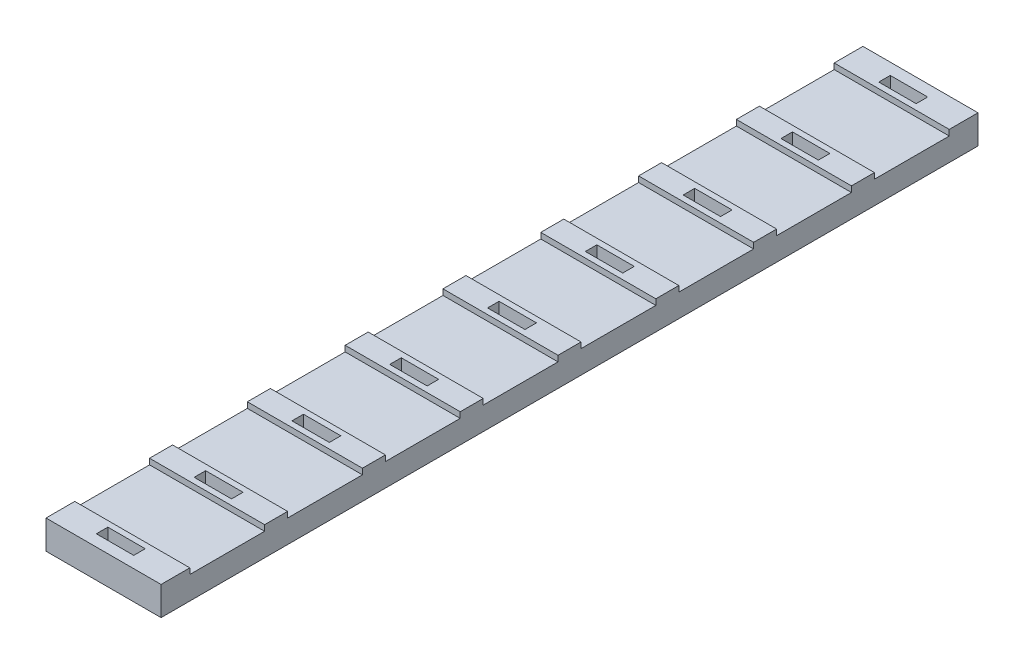
SolidWorks part; units mm, degrees
ref_plane "Front Plane" through (0, 0, 0) normal (0, 0, 1) x (1, 0, 0)
ref_plane "Top Plane" through (0, 0, 0) normal (0, 1, 0) x (1, 0, 0)
ref_plane "Right Plane" through (0, 0, 0) normal (1, 0, 0) x (0, 0, -1)
sketch "Sketch1" plane through (0, 0, 0) normal (0, 1, 0) x (1, 0, 0)
  line L1 (-10, -71) -> (10, -71)
  line L2 (-10, -71) -> (-10, 71)
  line L3 (-10, 71) -> (10, 71)
  line L4 (10, -71) -> (10, 71)
  line L5 (-10, -71) -> (10, 71) construction
  line L6 (-10, 71) -> (10, -71) construction
  point P0 (0, 0)
  dimension "D1" = 142
  dimension "D2" = 20
extrude "Boss-Extrude1" add sketch "Sketch1" along normal blind 7
sketch "Sketch2" plane through (0, 7, 0) normal (0, 1, 0) x (1, 0, 0)
  line L0 (-10, 71) -> (-10, -71) construction
  line L1 (-10, 66) -> (10, 66)
  line L2 (-10, 66) -> (-10, 53)
  line L3 (-10, 53) -> (10, 53)
  line L4 (10, 66) -> (10, 53)
  line L5 (10, -71) -> (10, 71) construction
  line L6 (10, 71) -> (-10, 71) construction
  dimension "D1" = 5
  dimension "D2" = 13
extrude "Cut-Extrude1" cut sketch "Sketch2" against normal blind 3
pattern_linear "LPattern1" count 8 spacing 17 along (0, 0, 1) of "Cut-Extrude1"
sketch "Sketch4" plane through (0, 7, 0) normal (0, 1, 0) x (1, 0, 0)
  line L0 (-3.25, 67) -> (-3.25, 66) construction
  line L1 (-3.25, 67) -> (3.25, 67)
  line L2 (-3.25, 67) -> (-3.25, 69)
  line L3 (-3.25, 69) -> (3.25, 69)
  line L4 (3.25, 67) -> (3.25, 69)
  line L5 (10, 66) -> (-10, 66) construction
  line L6 (-3.25, 67) -> (-10, 67) construction
  line L7 (-10, 71) -> (-10, 66) construction
  line L8 (3.25, 67) -> (10, 67) construction
  line L9 (10, 66) -> (10, 71) construction
  dimension "D1" = 1
  dimension "D2" = 2
  dimension "D3" = 6.5
extrude "Cut-Extrude2" cut sketch "Sketch4" against normal up to next
fillet "Fillet1" radius 0.5 2 edges at (0, 7, -69) (0, 7, -67)
chamfer "Chamfer1" distance 2 angle 45 18 edges at (10, 7, 68.5) (-10, 7, 68.5) (-10, 7, -68.5) (10, 7, -68.5) (-10, 7, 51) (10, 7, 51) (-10, 7, 34) (10, 7, 34) (-10, 7, 17) (10, 7, 17) (-10, 7, 0) (10, 7, 0) (-10, 7, -17) (10, 7, -17) (10, 7, -34) (-10, 7, -34) (-10, 7, -51) (10, 7, -51)
pattern_linear "LPattern2" count 9 spacing 17 along (0, 0, 1) of "Fillet1", "Cut-Extrude2"
sketch "Sketch5" plane through (0, 0, 0) normal (0, -1, 0) x (1, 0, 0)
  line L1 (-3.25, 67) -> (3.25, 67)
  line L2 (-3.25, 67) -> (-3.25, 52)
  line L3 (-3.25, 52) -> (3.25, 52)
  line L4 (3.25, 67) -> (3.25, 52)
extrude "Cut-Extrude3" cut sketch "Sketch5" against normal blind 2
pattern_linear "LPattern3" count 8 spacing 17 along (0, 0, -1) of "Cut-Extrude3"
sketch "Sketch6" plane through (0, 0, -71) normal (0, 0, -1) x (-1, 0, 0)
  line L0 (-8, 7) -> (8, 7) construction
  line L1 (-10, 5) -> (10, 5)
  line L2 (-10, 5) -> (-10, 7)
  line L3 (-10, 7) -> (10, 7)
  line L4 (10, 5) -> (10, 7)
  point P5 (0, 0)
extrude "Cut-Extrude4" cut sketch "Sketch6" against normal up to surface (142 mm away) up to face at (0, 4, 71)
